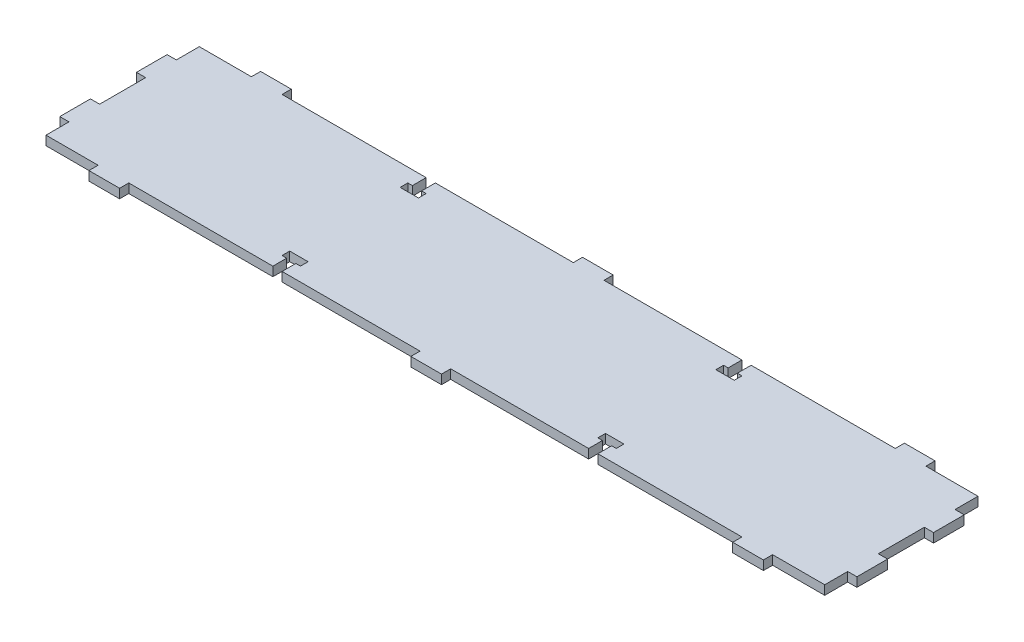
SolidWorks part; units mm, degrees
ref_plane "Front Plane" through (0, 0, 0) normal (0, 0, 1) x (1, 0, 0)
ref_plane "Top Plane" through (0, 0, 0) normal (0, 1, 0) x (1, 0, 0)
ref_plane "Right Plane" through (0, 0, 0) normal (1, 0, 0) x (0, 0, -1)
sketch "Sketch2" plane through (0, 0, 0) normal (0, 1, 0) x (1, 0, 0)
  line L0 (101.7071, 0) -> (-87.9643, 0) construction
  line L1 (0, 56.2207) -> (0, -52.9343) construction
  line L3 (-130, 28) -> (130, 28)
  line L4 (-130, 28) -> (-130, -28)
  line L5 (-130, -28) -> (130, -28)
  line L6 (130, 28) -> (130, -28)
  line L7 (-130, 28) -> (130, -28) construction
  line L8 (-130, -28) -> (130, 28) construction
  point P1 (0, 0)
  dimension "D1" = 56
  dimension "D2" = 260
extrude "Boss-Extrude1" add sketch "Sketch2" along normal blind 3
sketch "Sketch4" plane through (0, 3, 0) normal (0, 1, 0) x (1, 0, 0)
  line L0 (-100.9744, 0) -> (46.2082, 0) construction
  line L1 (0, 17.4913) -> (0, -13.3009) construction
  line L2 (-130, 28) -> (-130, -28) construction
  line L3 (-130, 7.5) -> (-127, 7.5)
  line L4 (-130, 7.5) -> (-130, -7.5)
  line L5 (-130, -7.5) -> (-127, -7.5)
  line L6 (-127, 7.5) -> (-127, -7.5)
  line L7 (-50, 25) -> (-50, 20.5)
  line L8 (-130, 28) -> (-130, 17.5)
  line L9 (-130, 17.5) -> (-127, 17.5)
  line L10 (-127, 17.5) -> (-127, 25)
  line L11 (-127, 25) -> (-110, 25)
  line L12 (-50, 20.5) -> (-48.5, 20.5)
  line L13 (-48.5, 20.5) -> (-48.5, 18)
  line L14 (-48.5, 18) -> (-54.5, 18)
  line L15 (-54.5, 18) -> (-54.5, 20.5)
  line L16 (-54.5, 20.5) -> (-53, 20.5)
  line L17 (-53, 20.5) -> (-53, 25)
  line L18 (-5, 25) -> (-50, 25)
  line L19 (-53, 25) -> (-100, 25)
  line L20 (110, 28) -> (130, 28)
  line L21 (110, 25) -> (110, 28)
  line L22 (5, 28) -> (5, 25)
  line L23 (127, 7.5) -> (127, -7.5)
  line L24 (130, -7.5) -> (127, -7.5)
  line L25 (130, 7.5) -> (130, -7.5)
  line L26 (130, 7.5) -> (127, 7.5)
  line L27 (130, 28) -> (-130, 28) construction
  line L28 (-100, 28) -> (-5, 28)
  line L29 (-100, 28) -> (-100, 25)
  line L30 (100, 28) -> (100, 25)
  line L31 (-5, 28) -> (-5, 25)
  line L32 (100, 28) -> (5, 28)
  line L33 (53, 25) -> (100, 25)
  line L34 (5, 25) -> (50, 25)
  line L35 (53, 20.5) -> (53, 25)
  line L36 (54.5, 20.5) -> (53, 20.5)
  line L37 (54.5, 18) -> (54.5, 20.5)
  line L38 (-110, 25) -> (-110, 28)
  line L39 (-110, 28) -> (-130, 28)
  line L40 (48.5, 18) -> (54.5, 18)
  line L41 (48.5, 20.5) -> (48.5, 18)
  line L42 (50, 20.5) -> (48.5, 20.5)
  line L43 (127, 25) -> (110, 25)
  line L44 (127, 17.5) -> (127, 25)
  line L45 (130, 17.5) -> (127, 17.5)
  line L46 (130, 28) -> (130, 17.5)
  line L47 (50, 25) -> (50, 20.5)
  line L48 (50, -25) -> (50, -20.5)
  line L49 (130, -28) -> (130, -17.5)
  line L50 (130, -17.5) -> (127, -17.5)
  line L51 (127, -17.5) -> (127, -25)
  line L52 (127, -25) -> (110, -25)
  line L53 (50, -20.5) -> (48.5, -20.5)
  line L54 (48.5, -20.5) -> (48.5, -18)
  line L55 (48.5, -18) -> (54.5, -18)
  line L56 (-110, -28) -> (-130, -28)
  line L57 (-110, -25) -> (-110, -28)
  line L58 (54.5, -18) -> (54.5, -20.5)
  line L59 (54.5, -20.5) -> (53, -20.5)
  line L60 (53, -20.5) -> (53, -25)
  line L61 (5, -25) -> (50, -25)
  line L62 (53, -25) -> (100, -25)
  line L63 (100, -28) -> (5, -28)
  line L64 (-5, -28) -> (-5, -25)
  line L65 (100, -28) -> (100, -25)
  line L66 (-100, -28) -> (-100, -25)
  line L67 (-100, -28) -> (-5, -28)
  line L68 (5, -28) -> (5, -25)
  line L69 (110, -25) -> (110, -28)
  line L70 (110, -28) -> (130, -28)
  line L71 (-53, -25) -> (-100, -25)
  line L72 (-5, -25) -> (-50, -25)
  line L73 (-53, -20.5) -> (-53, -25)
  line L74 (-54.5, -20.5) -> (-53, -20.5)
  line L75 (-54.5, -18) -> (-54.5, -20.5)
  line L76 (-48.5, -18) -> (-54.5, -18)
  line L77 (-48.5, -20.5) -> (-48.5, -18)
  line L78 (-50, -20.5) -> (-48.5, -20.5)
  line L79 (-127, -25) -> (-110, -25)
  line L80 (-127, -17.5) -> (-127, -25)
  line L81 (-130, -17.5) -> (-127, -17.5)
  line L82 (-130, -28) -> (-130, -17.5)
  line L83 (-50, -25) -> (-50, -20.5)
  dimension "D1" = 15
  dimension "D2" = 7.5
  dimension "D3" = 3
  dimension "D4" = 10
  dimension "D5" = 3
  dimension "D6" = 3
  dimension "D7" = 100
  dimension "D8" = 5
  dimension "D9" = 3
  dimension "D10" = 10
  dimension "D11" = 50
  dimension "D12" = 3
  dimension "D13" = 10
  dimension "D14" = 2.5
  dimension "D15" = 1.5
  dimension "D16" = 1.5
  dimension "D17" = 3
extrude "Cut-Extrude1" cut sketch "Sketch4" against normal through all
